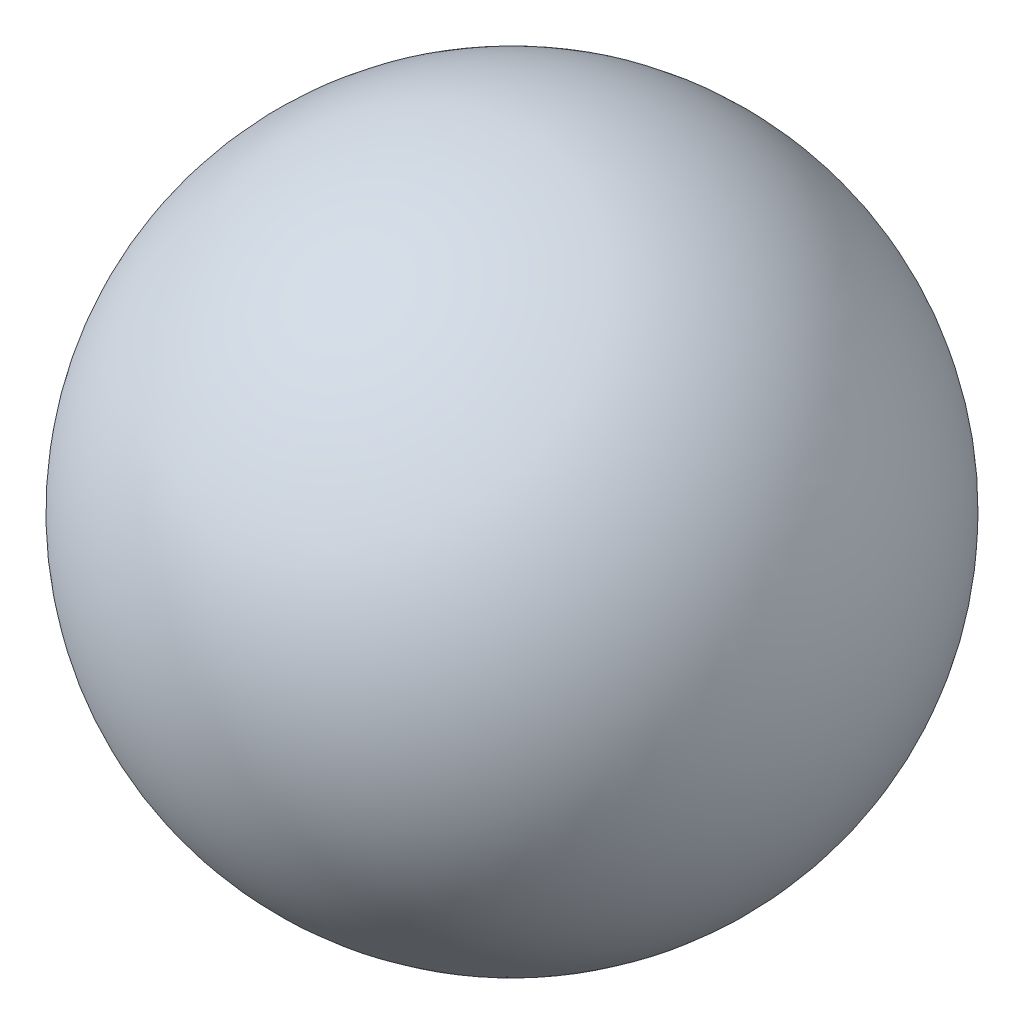
SolidWorks part; units mm, degrees
ref_plane "前视基准面" through (0, 0, 0) normal (0, 0, 1) x (1, 0, 0)
ref_plane "上视基准面" through (0, 0, 0) normal (0, 1, 0) x (1, 0, 0)
ref_plane "右视基准面" through (0, 0, 0) normal (1, 0, 0) x (0, 0, -1)
other "Configuration Table"
sketch "草图1" plane through (0, 0, 0) normal (0, 0, 1) x (1, 0, 0)
  line L0 (0, 11.8604) -> (0, -6.45) construction
  line L1 (0, 7) -> (0, -6.45)
  line L2 (0, -6.45) -> (2.7198, -6.45)
  arc A0 (2.7198, -6.45) -> (0, 7) centre (0, 0) ccw
  dimension "D1" = 7
  dimension "D2" = 6.45
revolve "旋转1" add sketch "草图1" angle 360 about L0
sketch "草图3" plane through (0, -6.45, 0) normal (0, -1, 0) x (1, 0, 0)
  circle A0 centre (0, 0) radius 2.5
  dimension "D1" = 5
extrude "切除-拉伸1" cut sketch "草图3" against normal blind 5
